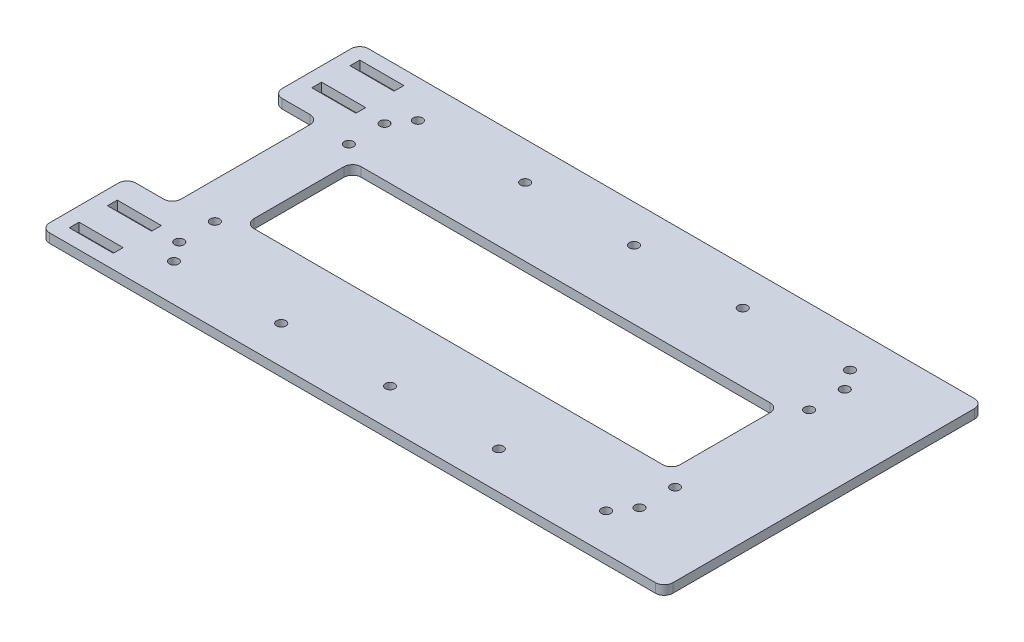
SolidWorks part; units mm, degrees
ref_plane "Front Plane" through (0, 0, 0) normal (0, 0, 1) x (1, 0, 0)
ref_plane "Top Plane" through (0, 0, 0) normal (0, 1, 0) x (1, 0, 0)
ref_plane "Right Plane" through (0, 0, 0) normal (1, 0, 0) x (0, 0, -1)
sketch "Sketch1" plane through (0, 0, 0) normal (0, 1, 0) x (1, 0, 0)
  line L1 (107.5, -55) -> (-107.5, -55)
  line L2 (107.5, -55) -> (107.5, 55)
  line L3 (107.5, 55) -> (-107.5, 55)
  line L4 (-107.5, -55) -> (-107.5, 55)
  line L5 (107.5, -55) -> (-107.5, 55) construction
  line L6 (107.5, 55) -> (-107.5, -55) construction
  point P0 (0, 0)
  dimension "D1" = 215
  dimension "D2" = 110
extrude "Boss-Extrude1" add sketch "Sketch1" along normal blind 3.175
sketch "Sketch2" plane through (0, 0, 0) normal (0, -1, 0) x (1, 0, 0)
  line L0 (71.5, -16.5) -> (71.5, 16.5) construction
  line L1 (-71.5, -16.5) -> (-71.5, 16.5) construction
  line L2 (71.5, -16.5) -> (-71.5, -16.5) construction
  line L3 (71.5, -16.5) -> (71.5, 16.5) construction
  line L4 (71.5, 16.5) -> (-71.5, 16.5)
  line L5 (-71.5, 16.5) -> (-71.5, -16.5)
  line L6 (-71.5, -16.5) -> (71.5, -16.5)
  line L7 (71.5, -16.5) -> (71.5, 16.5)
  line L8 (71.5, 16.5) -> (-71.5, 16.5) construction
  line L9 (-71.5, 16.5) -> (-71.5, -16.5) construction
  line L10 (-71.5, -16.5) -> (71.5, -16.5) construction
  line L11 (71.5, -16.5) -> (71.5, 16.5)
  line L12 (-71.5, -16.5) -> (-71.5, 16.5)
  line L13 (71.5, -16.5) -> (-71.5, -16.5)
  line L14 (73.5, -18.5) -> (73.5, 18.5)
  line L15 (73.5, 18.5) -> (-73.5, 18.5)
  line L16 (-73.5, 18.5) -> (-73.5, -18.5)
  line L17 (-73.5, -18.5) -> (73.5, -18.5)
  dimension "D1" = 0
  dimension "D2" = 2
extrude "Cut-Extrude1" cut sketch "Sketch2" against normal through all
sketch "Sketch3" plane through (0, 0, 0) normal (0, -1, 0) x (1, 0, 0)
  line L13 (-91.9, 25.25) -> (-107.5, 25.25)
  line L14 (-91.9, 25.25) -> (-91.9, -25.25)
  line L15 (-107.5, -25.25) -> (-91.9, -25.25)
  line L39 (-107.5, -25.25) -> (-107.5, 25.25)
extrude "Cut-Extrude2" cut sketch "Sketch3" against normal through all
sketch "Sketch5" plane through (0, 0, 0) normal (0, -1, 0) x (1, 0, 0)
  line L0 (-107.5, 23.1) -> (107.5, 23.1) construction
  line L1 (-107.5, 25.25) -> (-107.5, 55) construction
  line L2 (107.5, 55) -> (107.5, -55) construction
  line L3 (0, 0) -> (0, 55) construction
  line L4 (-107.5, 55) -> (107.5, 55) construction
  line L5 (0, 0) -> (-91.9, 0) construction
  line L6 (-91.9, -25.25) -> (-91.9, 25.25) construction
  line L7 (-79.375, 23.1) -> (-79.375, 55) construction
  circle A0 centre (-79.375, 23.1) radius 1.6
  circle A1 centre (-79.375, -23.1) radius 1.6
  circle A2 centre (79.375, -23.1) radius 1.6
  circle A3 centre (79.375, 23.1) radius 1.6
  circle A4 centre (-79.375, 35.4) radius 1.6
  circle A5 centre (-79.375, -35.4) radius 1.6
  circle A6 centre (79.375, 35.4) radius 1.6
  circle A7 centre (79.375, -35.4) radius 1.6
  dimension "D3" = 3.2
  dimension "D4" = 12.3
  dimension "D1" = 23.1
  dimension "D2" = 79.375
extrude "Cut-Extrude4" cut sketch "Sketch5" against normal through all
sketch "Sketch6" plane through (0, 3.175, 0) normal (0, 1, 0) x (1, 0, 0)
  circle A0 centre (37.5283, 42.0689) radius 1.6 construction
  circle A1 centre (0, 42.0689) radius 1.6 construction
  circle A2 centre (-37.5283, 42.0689) radius 1.6 construction
  circle A3 centre (-74.5283, 42.0689) radius 1.6 construction
  circle A4 centre (74.5283, -42.0689) radius 1.6 construction
  circle A5 centre (37.5283, -42.0689) radius 1.6 construction
  circle A6 centre (0, -42.0689) radius 1.6 construction
  circle A7 centre (-37.5283, -42.0689) radius 1.6 construction
  circle A8 centre (-74.5283, -42.0689) radius 1.6 construction
  circle A9 centre (37.5283, 42.0689) radius 1.6
  circle A10 centre (0, 42.0689) radius 1.6
  circle A11 centre (-37.5283, 42.0689) radius 1.6
  circle A12 centre (-74.5283, 42.0689) radius 1.6
  circle A13 centre (74.5283, -42.0689) radius 1.6
  circle A14 centre (37.5283, -42.0689) radius 1.6
  circle A15 centre (0, -42.0689) radius 1.6
  circle A16 centre (-37.5283, -42.0689) radius 1.6
  circle A17 centre (-74.5283, -42.0689) radius 1.6
  circle A18 centre (74.5283, 42.0689) radius 1.6 construction
  circle A19 centre (74.5283, 42.0689) radius 1.6
extrude "Cut-Extrude5" cut sketch "Sketch6" against normal through all
fillet "Fillet1" radius 3 12 edges at (-107.5, 1.5875, -55) (-107.5, 1.5875, -25.25) (107.5, 1.5875, -55) (107.5, 1.5875, 55) (-107.5, 1.5875, 55) (-107.5, 1.5875, 25.25) (-91.9, 1.5875, 25.25) (-91.9, 1.5875, -25.25) (73.5, 1.5875, -18.5) (73.5, 1.5875, 18.5) (-73.5, 1.5875, -18.5) (-73.5, 1.5875, 18.5)
sketch "Sketch7" plane through (0, 0, 0) normal (0, -1, 0) x (1, 0, 0)
  line L0 (-87.5, -46.825) -> (-88.5, -46.825) construction
  line L1 (-88.5, -50) -> (-87.5, -50) construction
  line L2 (-87.5, -50) -> (-87.5, -46.825) construction
  line L3 (-88.5, -46.825) -> (-101.5, -46.825) construction
  line L4 (-101.5, -50) -> (-88.5, -50) construction
  line L5 (-101.5, -46.825) -> (-102.5, -46.825) construction
  line L6 (-102.5, -46.825) -> (-102.5, -50) construction
  line L7 (-102.5, -50) -> (-101.5, -50) construction
  line L8 (-101.5, -33.65) -> (-102.5, -33.65) construction
  line L9 (-102.5, -33.65) -> (-102.5, -36.825) construction
  line L10 (-102.5, -36.825) -> (-101.5, -36.825) construction
  line L11 (-88.5, -33.65) -> (-101.5, -33.65) construction
  line L12 (-101.5, -36.825) -> (-88.5, -36.825) construction
  line L13 (-87.5, -33.65) -> (-88.5, -33.65) construction
  line L14 (-88.5, -36.825) -> (-87.5, -36.825) construction
  line L15 (-87.5, -36.825) -> (-87.5, -33.65) construction
  line L16 (-87.5, 50) -> (-88.5, 50) construction
  line L17 (-88.5, 46.825) -> (-87.5, 46.825) construction
  line L18 (-87.5, 46.825) -> (-87.5, 50) construction
  line L19 (-88.5, 50) -> (-101.5, 50) construction
  line L20 (-101.5, 46.825) -> (-88.5, 46.825) construction
  line L21 (-101.5, 50) -> (-102.5, 50) construction
  line L22 (-102.5, 50) -> (-102.5, 46.825) construction
  line L23 (-102.5, 46.825) -> (-101.5, 46.825) construction
  line L24 (-101.5, 36.825) -> (-102.5, 36.825) construction
  line L25 (-102.5, 36.825) -> (-102.5, 33.65) construction
  line L26 (-102.5, 33.65) -> (-101.5, 33.65) construction
  line L27 (-88.5, 36.825) -> (-101.5, 36.825) construction
  line L28 (-101.5, 33.65) -> (-88.5, 33.65) construction
  line L29 (-87.5, 36.825) -> (-88.5, 36.825) construction
  line L30 (-88.5, 33.65) -> (-87.5, 33.65) construction
  line L31 (-87.5, 33.65) -> (-87.5, 36.825) construction
  line L32 (-87.5, -46.825) -> (-88.5, -46.825) construction
  line L33 (-88.5, -50) -> (-87.5, -50) construction
  line L34 (-87.5, -50) -> (-87.5, -46.825) construction
  line L35 (-88.5, -46.825) -> (-101.5, -46.825) construction
  line L36 (-101.5, -50) -> (-88.5, -50) construction
  line L37 (-101.5, -46.825) -> (-102.5, -46.825) construction
  line L38 (-102.5, -46.825) -> (-102.5, -50) construction
  line L39 (-102.5, -50) -> (-101.5, -50) construction
  line L40 (-101.5, -33.65) -> (-102.5, -33.65) construction
  line L41 (-102.5, -33.65) -> (-102.5, -36.825) construction
  line L42 (-102.5, -36.825) -> (-101.5, -36.825) construction
  line L43 (-88.5, -33.65) -> (-101.5, -33.65) construction
  line L44 (-101.5, -36.825) -> (-88.5, -36.825) construction
  line L45 (-87.5, -33.65) -> (-88.5, -33.65) construction
  line L46 (-88.5, -36.825) -> (-87.5, -36.825) construction
  line L47 (-87.5, -36.825) -> (-87.5, -33.65) construction
  line L48 (-87.5, 50) -> (-88.5, 50) construction
  line L49 (-88.5, 46.825) -> (-87.5, 46.825) construction
  line L50 (-87.5, 46.825) -> (-87.5, 50) construction
  line L51 (-88.5, 50) -> (-101.5, 50) construction
  line L52 (-101.5, 46.825) -> (-88.5, 46.825) construction
  line L53 (-101.5, 50) -> (-102.5, 50) construction
  line L54 (-102.5, 50) -> (-102.5, 46.825) construction
  line L55 (-102.5, 46.825) -> (-101.5, 46.825) construction
  line L56 (-101.5, 36.825) -> (-102.5, 36.825) construction
  line L57 (-102.5, 36.825) -> (-102.5, 33.65) construction
  line L58 (-102.5, 33.65) -> (-101.5, 33.65) construction
  line L59 (-88.5, 36.825) -> (-101.5, 36.825) construction
  line L60 (-101.5, 33.65) -> (-88.5, 33.65) construction
  line L61 (-87.5, 36.825) -> (-88.5, 36.825) construction
  line L62 (-88.5, 33.65) -> (-87.5, 33.65) construction
  line L63 (-87.5, 33.65) -> (-87.5, 36.825) construction
  line L64 (-87.4, -46.725) -> (-88.5, -46.725)
  line L65 (-88.5, -46.725) -> (-101.5, -46.725)
  line L66 (-101.5, -46.725) -> (-102.6, -46.725)
  line L67 (-102.6, -46.725) -> (-102.6, -50.1)
  line L68 (-102.6, -50.1) -> (-101.5, -50.1)
  line L69 (-101.5, -50.1) -> (-88.5, -50.1)
  line L70 (-88.5, -50.1) -> (-87.4, -50.1)
  line L71 (-87.4, -50.1) -> (-87.4, -46.725)
  line L72 (-101.5, -33.55) -> (-102.6, -33.55)
  line L73 (-102.6, -33.55) -> (-102.6, -36.925)
  line L74 (-102.6, -36.925) -> (-101.5, -36.925)
  line L75 (-101.5, -36.925) -> (-88.5, -36.925)
  line L76 (-88.5, -36.925) -> (-87.4, -36.925)
  line L77 (-87.4, -36.925) -> (-87.4, -33.55)
  line L78 (-87.4, -33.55) -> (-88.5, -33.55)
  line L79 (-88.5, -33.55) -> (-101.5, -33.55)
  line L80 (-87.4, 50.1) -> (-88.5, 50.1)
  line L81 (-88.5, 50.1) -> (-101.5, 50.1)
  line L82 (-101.5, 50.1) -> (-102.6, 50.1)
  line L83 (-102.6, 50.1) -> (-102.6, 46.725)
  line L84 (-102.6, 46.725) -> (-101.5, 46.725)
  line L85 (-101.5, 46.725) -> (-88.5, 46.725)
  line L86 (-88.5, 46.725) -> (-87.4, 46.725)
  line L87 (-87.4, 46.725) -> (-87.4, 50.1)
  line L88 (-101.5, 36.925) -> (-102.6, 36.925)
  line L89 (-102.6, 36.925) -> (-102.6, 33.55)
  line L90 (-102.6, 33.55) -> (-101.5, 33.55)
  line L91 (-101.5, 33.55) -> (-88.5, 33.55)
  line L92 (-88.5, 33.55) -> (-87.4, 33.55)
  line L93 (-87.4, 33.55) -> (-87.4, 36.925)
  line L94 (-87.4, 36.925) -> (-88.5, 36.925)
  line L95 (-88.5, 36.925) -> (-101.5, 36.925)
  dimension "D1" = 0.1
extrude "Cut-Extrude6" cut sketch "Sketch7" against normal through all
